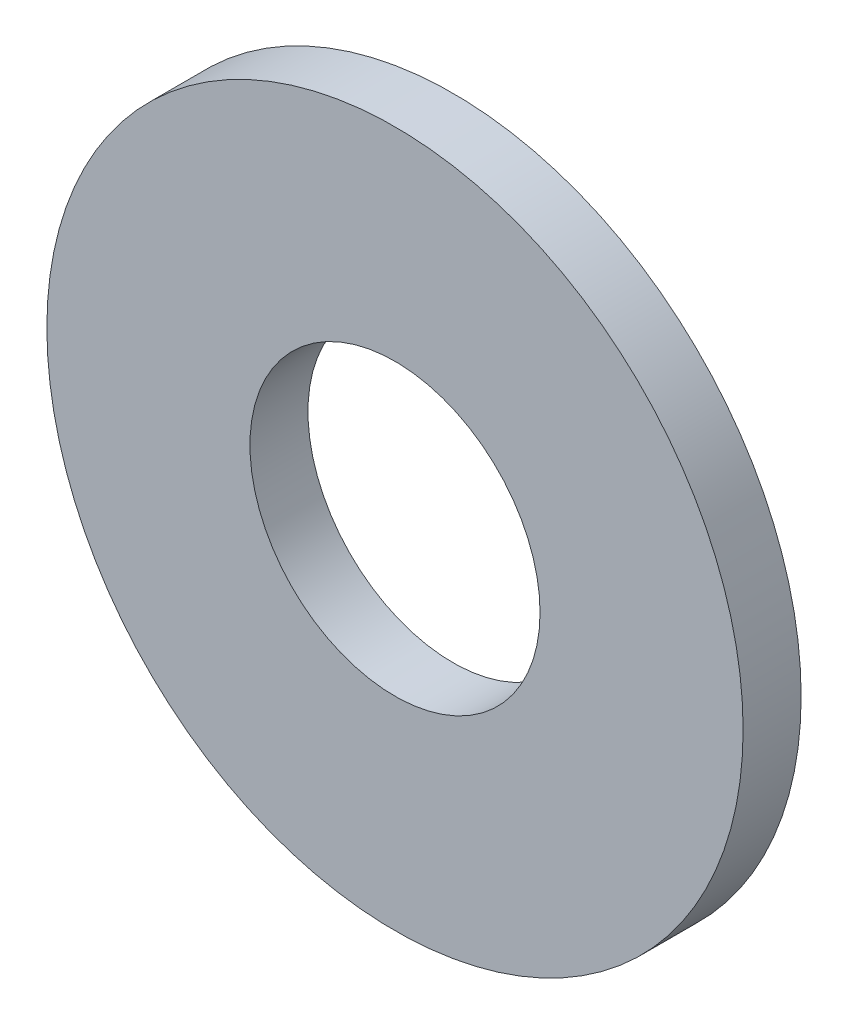
SolidWorks part; units mm, degrees
ref_plane "Спереди" through (0, 0, 0) normal (0, 0, 1) x (1, 0, 0)
ref_plane "Сверху" through (0, 0, 0) normal (0, 1, 0) x (1, 0, 0)
ref_plane "Справа" through (0, 0, 0) normal (1, 0, 0) x (0, 0, -1)
sketch "Эскиз1" plane through (0, 0, 0) normal (0, 0, 1) x (1, 0, 0)
  circle A0 centre (0, 0) radius 5
  circle A1 centre (0, 0) radius 12
extrude "Вытянуть1" add sketch "Эскиз1" along normal blind 2
